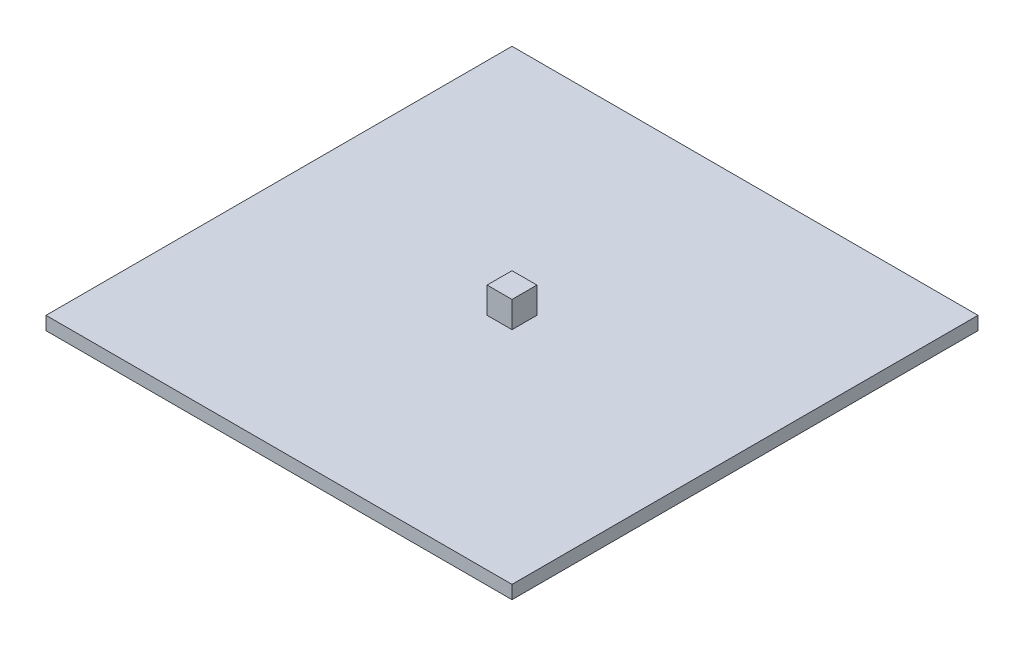
SolidWorks part; units mm, degrees
ref_plane "Front Plane" through (0, 0, 0) normal (0, 0, 1) x (1, 0, 0)
ref_plane "Top Plane" through (0, 0, 0) normal (0, 1, 0) x (1, 0, 0)
ref_plane "Right Plane" through (0, 0, 0) normal (1, 0, 0) x (0, 0, -1)
sketch "Sketch1" plane through (0, 0, 0) normal (0, 1, 0) x (1, 0, 0)
  line L1 (-44.45, -44.45) -> (44.45, -44.45)
  line L2 (-44.45, -44.45) -> (-44.45, 44.45)
  line L3 (-44.45, 44.45) -> (44.45, 44.45)
  line L4 (44.45, -44.45) -> (44.45, 44.45)
  line L5 (-44.45, -44.45) -> (44.45, 44.45) construction
  line L6 (-44.45, 44.45) -> (44.45, -44.45) construction
  point P0 (0, 0)
  dimension "D1" = 88.9
  dimension "D2" = 88.9
extrude "Boss-Extrude1" add sketch "Sketch1" along normal blind 2.54
sketch "Sketch2" plane through (0, 2.54, 0) normal (0, 1, 0) x (1, 0, 0)
  line L0 (0, 44.45) -> (0, -44.45) construction
  line L1 (2.375, -2.375) -> (2.375, 2.375)
  line L2 (2.375, -2.375) -> (-2.375, -2.375)
  line L3 (-2.375, -2.375) -> (-2.375, 2.375)
  line L4 (2.375, 2.375) -> (-2.375, 2.375)
  line L5 (2.375, -2.375) -> (-2.375, 2.375) construction
  line L6 (-2.375, -2.375) -> (2.375, 2.375) construction
  line L7 (44.45, 44.45) -> (-44.45, 44.45) construction
  line L8 (-44.45, -44.45) -> (44.45, -44.45) construction
  point P0 (0, 0)
  point P6 (-2.3955, 2.3544)
  dimension "D1" = 4.75
extrude "Boss-Extrude2" add sketch "Sketch2" along normal blind 5
